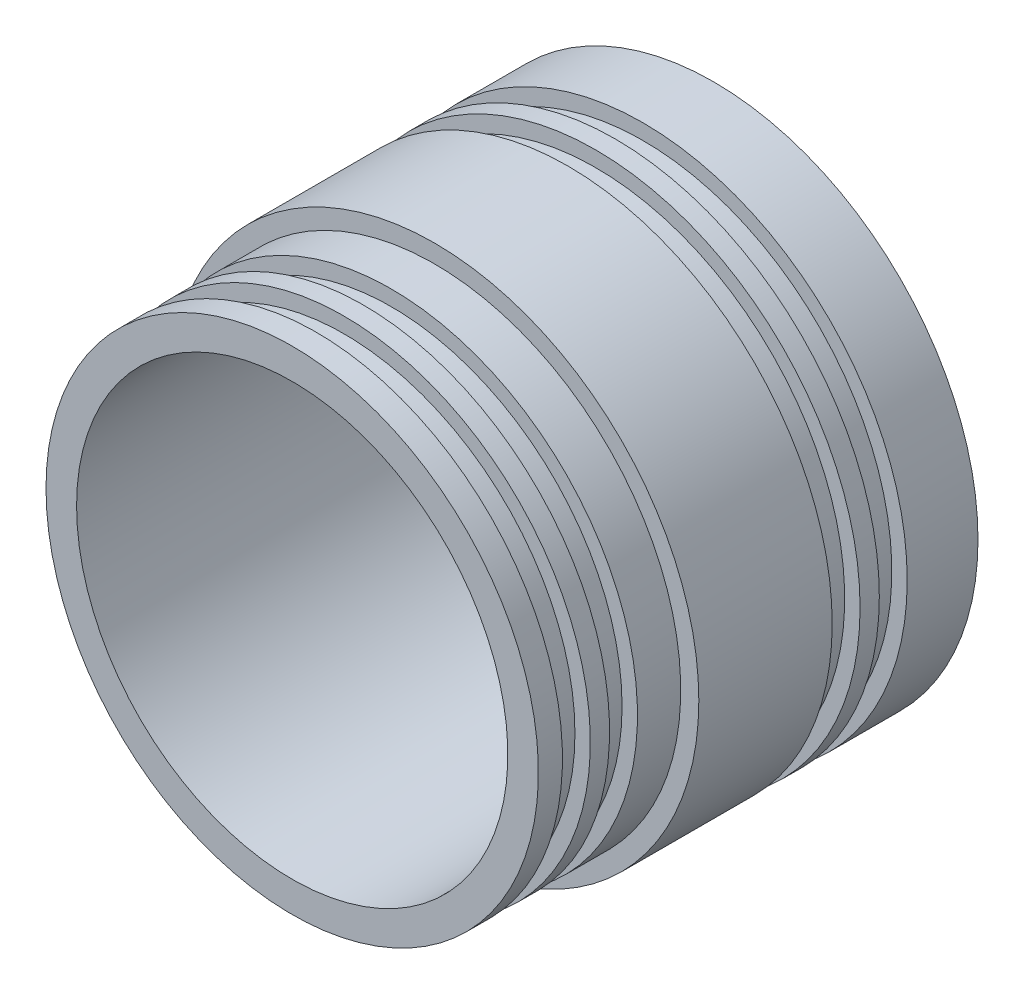
SolidWorks part; units mm, degrees
material "6061-T6 (SS)"
ref_plane "Front Plane" through (0, 0, 0) normal (0, 0, 1) x (1, 0, 0)
ref_plane "Top Plane" through (0, 0, 0) normal (0, 1, 0) x (1, 0, 0)
ref_plane "Right Plane" through (0, 0, 0) normal (1, 0, 0) x (0, 0, -1)
sketch "Sketch1" plane through (0, 0, 0) normal (1, 0, 0) x (0, 0, -1)
  line L0 (0, 28.4734) -> (0, 32.8676)
  line L4 (-49.4894, 32.512) -> (-49.4894, 28.4734)
  line L5 (-49.4894, 28.4734) -> (0, 28.4734)
  line L6 (0, 0) -> (-50000, 0) construction
  line L7 (-49.4894, 32.512) -> (-46.3144, 32.512)
  line L8 (-46.3144, 32.512) -> (-46.3144, 30.48)
  line L9 (-46.3144, 30.48) -> (-42.6314, 30.48)
  line L10 (-42.6314, 30.48) -> (-42.6314, 32.512)
  line L11 (-42.6314, 32.512) -> (-40.0914, 32.512)
  line L12 (-40.0914, 32.512) -> (-40.0914, 30.48)
  line L13 (-40.0914, 30.48) -> (-36.4084, 30.48)
  line L14 (-36.4084, 30.48) -> (-36.4084, 32.512)
  line L15 (-36.4084, 32.512) -> (-30.6934, 32.512)
  line L16 (-30.6934, 32.512) -> (-30.6934, 34.8996)
  line L17 (-30.6934, 34.8996) -> (-13.081, 34.8996)
  line L18 (-13.081, 34.8996) -> (-13.081, 32.8676)
  line L19 (-13.081, 32.8676) -> (-9.398, 32.8676)
  line L20 (-9.398, 32.8676) -> (-9.398, 34.8996)
  line L21 (-9.398, 34.8996) -> (-6.858, 34.8996)
  line L22 (-6.858, 34.8996) -> (-6.858, 32.8676)
  line L23 (-6.858, 32.8676) -> (-3.175, 32.8676)
  line L24 (-3.175, 32.8676) -> (-3.175, 34.8996)
  line L25 (-3.175, 34.8996) -> (6.1722, 34.8996)
  line L26 (6.1722, 34.8996) -> (6.1722, 32.8676)
  line L27 (6.1722, 32.8676) -> (0, 32.8676)
  point P1 (-30.6934, 33.7058)
  dimension "D1" = 3.175
  dimension "D2" = 2.54
  dimension "D3" = 49.4894
  dimension "D4" = 2.54
  dimension "D5" = 56.9468
  dimension "D6" = 3.175
  dimension "D7" = 6.1722
  dimension "D8" = 2.032
  dimension "D9" = 2.032
  dimension "D10" = 65.024
  dimension "D11" = 69.7992
  dimension "D12" = 36.8656
  dimension "D13" = 3.683
revolve "Revolve1 (O-Rings : 2-141 & 2-144)" add sketch "Sketch1" angle 360 about L6
